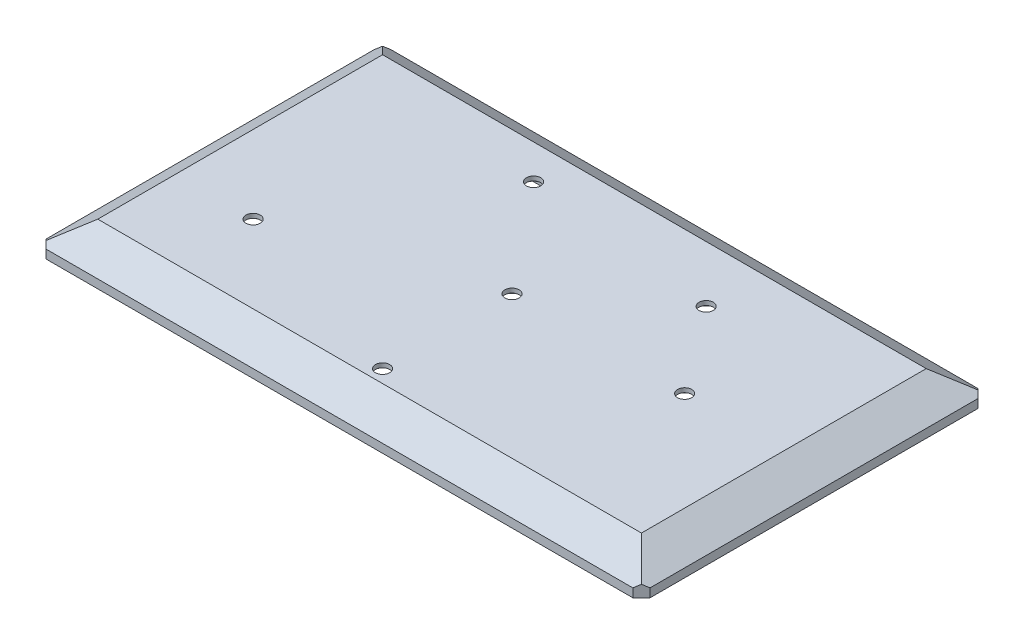
SolidWorks part; units mm, degrees
ref_plane "Front Plane" through (0, 0, 0) normal (0, 0, 1) x (1, 0, 0)
ref_plane "Top Plane" through (0, 0, 0) normal (0, 1, 0) x (1, 0, 0)
ref_plane "Right Plane" through (0, 0, 0) normal (1, 0, 0) x (0, 0, -1)
sketch "Sketch1" plane through (0, 0, 0) normal (0, 1, 0) x (1, 0, 0)
  line L1 (-70, -40) -> (70, -40)
  line L2 (-70, -40) -> (-70, 40)
  line L3 (-70, 40) -> (70, 40)
  line L4 (70, -40) -> (70, 40)
  line L5 (-70, -40) -> (70, 40) construction
  line L6 (-70, 40) -> (70, -40) construction
  point P0 (0, 0)
  dimension "D1" = 140
  dimension "D2" = 80
extrude "Boss-Extrude1" add sketch "Sketch1" along normal blind 2
sketch "Sketch2" plane through (0, 2, 0) normal (0, 1, 0) x (1, 0, 0)
  line L4 (70, -40) -> (70, 40)
  line L5 (70, 40) -> (-70, 40)
  line L6 (-70, 40) -> (-70, -40)
  line L7 (-70, -40) -> (70, -40)
  line L8 (70, -40) -> (70, 40)
  line L9 (70, 40) -> (-70, 40)
  line L10 (-70, 40) -> (-70, -40)
  line L11 (-70, -40) -> (70, -40)
  dimension "D1" = 0
ref_plane "Plane1" through (0, 7, 0) normal (0, 1, 0) x (1, 0, 0)
sketch "Sketch3" plane through (0, 7, 0) normal (0, 1, 0) x (1, 0, 0)
  line L0 (-70, 40) -> (-70, -40) construction
  line L1 (-63, -33) -> (63, -33)
  line L2 (-63, -33) -> (-63, 33)
  line L3 (-63, 33) -> (63, 33)
  line L4 (63, -33) -> (63, 33)
  line L5 (-63, -33) -> (63, 33) construction
  line L6 (-63, 33) -> (63, -33) construction
  line L7 (70, 40) -> (-70, 40) construction
  point P0 (0, 0)
  dimension "D1" = 7
  dimension "D2" = 7
loft "Loft1" add profiles "Sketch3", "Sketch2"
chamfer "Chamfer2" distance 2 angle 45 4 edges at (70, 1, 40) (70, 1, -40) (-70, 1, -40) (-70, 1, 40)
sketch "Sketch4" plane through (0, 0, 0) normal (0, -1, 0) x (1, 0, 0)
  line L0 (-70, -38) -> (-70, 38) construction
  line L1 (-62.9, 15) -> (-54.9, 15)
  line L2 (-62.9, 15) -> (-62.9, 25)
  line L3 (-62.9, 25) -> (-54.9, 25)
  line L4 (-54.9, 15) -> (-54.9, 25)
  line L5 (-62.9, 15) -> (-54.9, 25) construction
  line L6 (-62.9, 25) -> (-54.9, 15) construction
  line L7 (-70, 0) -> (70, 0) construction
  line L8 (70, 38) -> (70, -38) construction
  line L9 (0, 40) -> (0, -40) construction
  line L10 (-68, 40) -> (68, 40) construction
  line L11 (68, -40) -> (-68, -40) construction
  line L12 (-62.9, -25) -> (-54.9, -15) construction
  line L13 (-62.9, -15) -> (-54.9, -25) construction
  line L14 (-54.9, -15) -> (-54.9, -25)
  line L15 (-62.9, -25) -> (-54.9, -25)
  line L16 (-62.9, -15) -> (-62.9, -25)
  line L17 (-62.9, -15) -> (-54.9, -15)
  line L18 (62.9, -15) -> (54.9, -25) construction
  line L19 (62.9, -25) -> (54.9, -15) construction
  line L20 (62.9, 25) -> (54.9, 15) construction
  line L21 (62.9, 15) -> (54.9, 25) construction
  line L22 (62.9, -15) -> (54.9, -15)
  line L23 (62.9, -15) -> (62.9, -25)
  line L24 (62.9, -25) -> (54.9, -25)
  line L25 (54.9, -15) -> (54.9, -25)
  line L26 (54.9, 15) -> (54.9, 25)
  line L27 (62.9, 25) -> (54.9, 25)
  line L28 (62.9, 15) -> (62.9, 25)
  line L29 (62.9, 15) -> (54.9, 15)
  point P0 (-58.9, 20)
  point P21 (-58.9, -20)
  point P30 (58.9, -20)
  point P31 (58.9, 20)
  dimension "D1" = 10
  dimension "D2" = 7.1
  dimension "D3" = 8
  dimension "D4" = 40
extrude "Boss-Extrude2" add sketch "Sketch4" along normal blind 7
sketch "Sketch5" plane through (-62.9, 0, 0) normal (-1, 0, 0) x (0, 0, 1)
  line L0 (-15, 0) -> (-25, -7) construction
  line L1 (0, 0) -> (0, 50000) construction
  circle A0 centre (-20, -3.5) radius 2.05
  circle A1 centre (20, -3.5) radius 2.05
  dimension "D1" = 4.1
extrude "Cut-Extrude1" cut sketch "Sketch5" against normal through all
sketch "Sketch6" plane through (0, 0, 0) normal (0, -1, 0) x (1, 0, 0)
  line L0 (54.9, 25) -> (54.9, 15) construction
  line L1 (-53.9, -32) -> (53.9, -32)
  line L2 (-53.9, -32) -> (-53.9, 32)
  line L3 (-53.9, 32) -> (53.9, 32)
  line L4 (53.9, -32) -> (53.9, 32)
  line L5 (-53.9, -32) -> (53.9, 32) construction
  line L6 (-53.9, 32) -> (53.9, -32) construction
  line L8 (-63, 33) -> (63, 33) construction
  point P0 (0, 0)
  dimension "D1" = 1
  dimension "D2" = 1
extrude "Cut-Extrude2" cut sketch "Sketch6" against normal offset from surface (5 mm away) 2 up to face at (0, 7, 0)
sketch "Sketch7" plane through (0, 5, 0) normal (0, -1, 0) x (1, 0, 0)
  line L0 (0, 0) -> (0, 30) construction
  line L1 (0, 0) -> (40, 0) construction
  line L2 (0, 0) -> (25, -20) construction
  line L3 (0, 0) -> (-45, 15) construction
  line L4 (0, 0) -> (-20, -25) construction
  circle A0 centre (0, 30) radius 1.65
  circle A1 centre (40, 0) radius 1.65
  circle A2 centre (25, -20) radius 1.65
  circle A3 centre (-20, -25) radius 1.65
  circle A5 centre (-45, 15) radius 1.65
  circle A6 centre (0, 0) radius 1.65
  dimension "D1" = 3.3
  dimension "D5" = 20
  dimension "D6" = 45
  dimension "D2" = 30
  dimension "D3" = 40
  dimension "D4" = 25
  dimension "D7" = 20
  dimension "D8" = 25
  dimension "D9" = 15
extrude "Cut-Extrude3" cut sketch "Sketch7" against normal through all
sketch "Sketch8" plane through (0, 5, 0) normal (0, -1, 0) x (1, 0, 0)
  circle A0 centre (0, 30) radius 3
  circle A1 centre (40, 0) radius 3
  circle A2 centre (25, -20) radius 3
  circle A3 centre (0, 0) radius 3
  circle A4 centre (-45, 15) radius 3
  circle A5 centre (-20, -25) radius 3
  dimension "D1" = 6
extrude "Cut-Extrude4" cut sketch "Sketch8" against normal blind 1 and the other way through all
